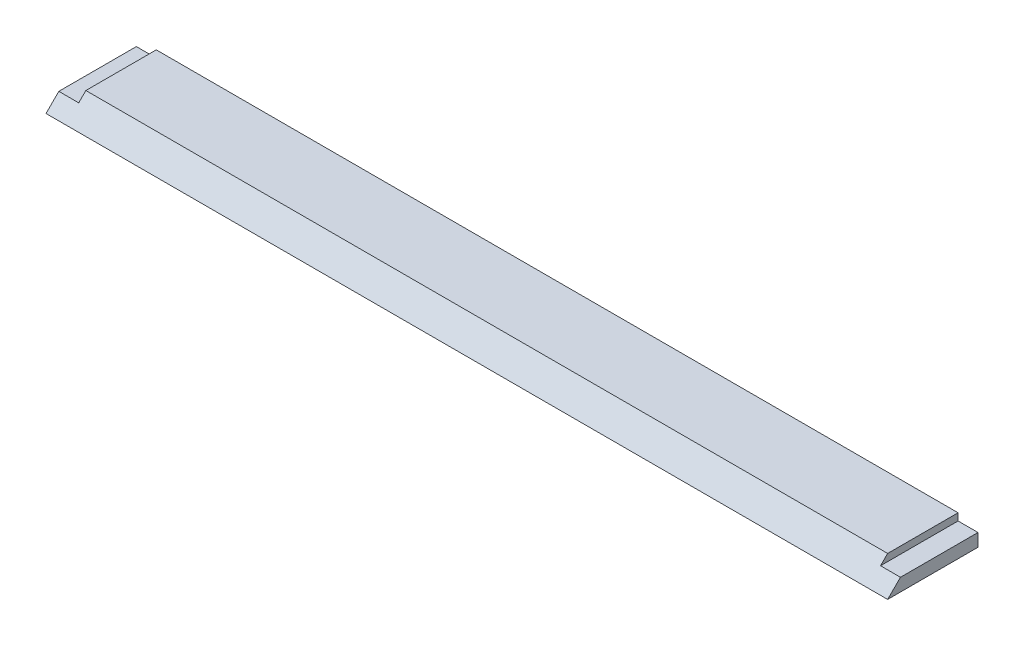
SolidWorks part; units mm, degrees
material "柚木"
ref_plane "前视基准面" through (0, 0, 0) normal (0, 0, 1) x (1, 0, 0)
ref_plane "上视基准面" through (0, 0, 0) normal (0, 1, 0) x (1, 0, 0)
ref_plane "右视基准面" through (0, 0, 0) normal (1, 0, 0) x (0, 0, -1)
sketch "草图1" plane through (0, 0, 0) normal (0, 1, 0) x (1, 0, 0)
  line L1 (-32.3514, 17.9864) -> (85.9486, 17.9864)
  line L2 (-32.3514, 17.9864) -> (-32.3514, 5.2864)
  line L3 (-32.3514, 5.2864) -> (85.9486, 5.2864)
  line L4 (85.9486, 17.9864) -> (85.9486, 5.2864)
  dimension "D1" = 118.3
  dimension "D2" = 12.7
extrude "凸台-拉伸1" add sketch "草图1" along normal blind 2.8
sketch "草图2" plane through (0, 2.8, 0) normal (0, 1, 0) x (1, 0, 0)
  line L0 (-32.3514, 5.2864) -> (85.9486, 5.2864) construction
  line L1 (-32.3514, 17.9864) -> (-29.5514, 17.9864)
  line L2 (-32.3514, 17.9864) -> (-32.3514, 5.2864)
  line L3 (-32.3514, 5.2864) -> (-29.5514, 5.2864)
  line L4 (-29.5514, 17.9864) -> (-29.5514, 5.2864)
  line L6 (85.9486, 17.9864) -> (83.1486, 17.9864)
  line L7 (85.9486, 17.9864) -> (85.9486, 5.2864)
  line L8 (85.9486, 5.2864) -> (83.1486, 5.2864)
  line L9 (83.1486, 17.9864) -> (83.1486, 5.2864)
  dimension "D1" = 2.8
  dimension "D2" = 2.8
extrude "切除-拉伸1" cut sketch "草图2" against normal blind 1
sketch "草图3" plane through (85.9486, 0, 0) normal (1, 0, 0) x (0, 0, -1)
  line L0 (5.2864, 0) -> (5.2864, 2.8)
  line L1 (5.2864, 2.8) -> (8.0864, 2.8)
  line L2 (17.9864, 2.8) -> (5.2864, 2.8) construction
  line L3 (8.0864, 2.8) -> (5.2864, 0)
  dimension "D1" = 45
extrude "切除-拉伸2" cut sketch "草图3" against normal through all
